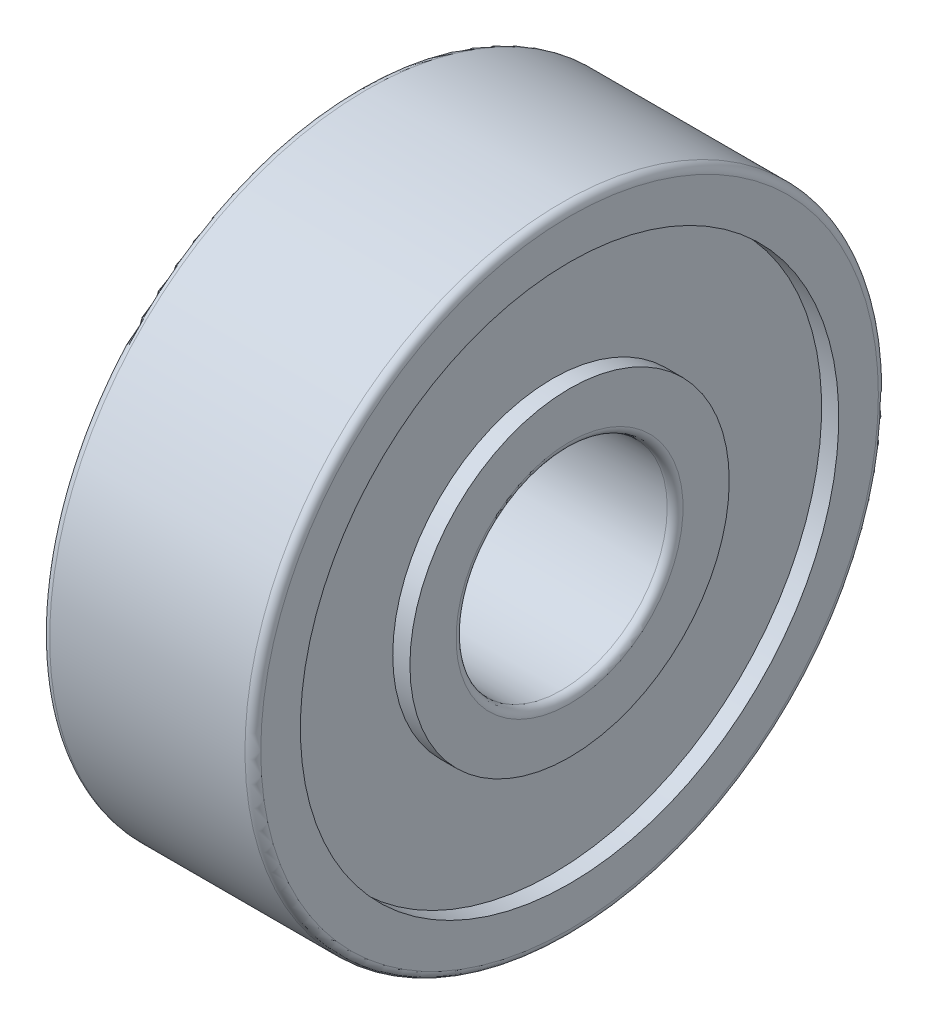
SolidWorks part; units mm, degrees
ref_plane "Front Plane" through (0, 0, 0) normal (0, 0, 1) x (1, 0, 0)
ref_plane "Top Plane" through (0, 0, 0) normal (0, 1, 0) x (1, 0, 0)
ref_plane "Right Plane" through (0, 0, 0) normal (1, 0, 0) x (0, 0, -1)
sketch "Sketch1" plane through (0, 0, 0) normal (0, 0, 1) x (1, 0, 0)
  line L0 (0, 0) -> (8, 0) construction
  line L1 (0, 4) -> (0, 6.05)
  line L2 (0, 6.05) -> (0.65, 6.05)
  line L3 (0.65, 6.05) -> (0.65, 10.2)
  line L4 (0.65, 10.2) -> (0, 10.2)
  line L5 (0, 10.2) -> (0, 12)
  line L6 (0, 12) -> (8, 12)
  line L7 (8, 12) -> (8, 10.2)
  line L8 (8, 10.2) -> (7.35, 10.2)
  line L9 (7.35, 10.2) -> (7.35, 6.05)
  line L10 (7.35, 6.05) -> (8, 6.05)
  line L11 (8, 6.05) -> (8, 4)
  line L12 (8, 4) -> (0, 4)
  dimension "D_s" = 8
  dimension "D" = 24
  dimension "B" = 8
  dimension "MSM_3" = 12.1
  dimension "MSM_4" = 20.4
  dimension "MSM_5" = 6.7
revolve "Revolve1" add sketch "Sketch1" angle 360 about L0
fillet "Fillet1" radius 0.3 4 edges at (0, -4, 0) (8, -4, 0) (0, -12, 0) (8, -12, 0)
